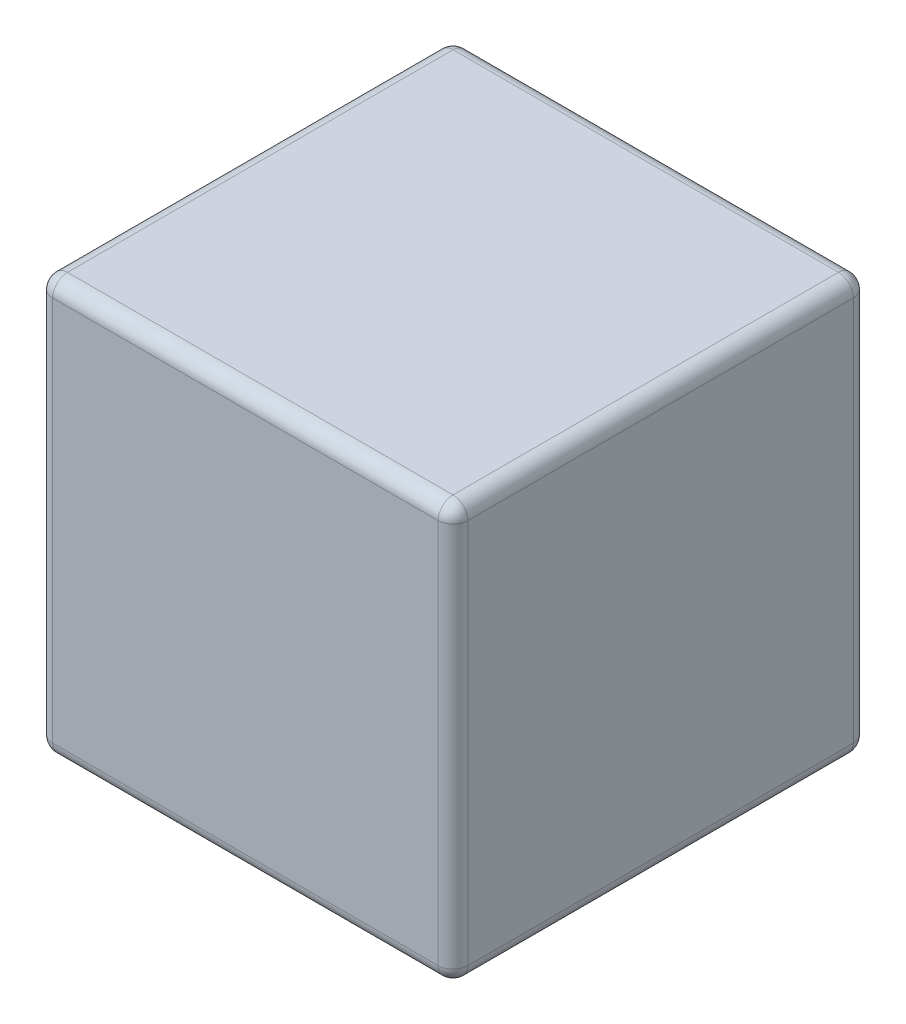
SolidWorks part; units mm, degrees
ref_plane "Front" through (0, 0, 0) normal (0, 0, 1) x (1, 0, 0)
ref_plane "Top" through (0, 0, 0) normal (0, 1, 0) x (1, 0, 0)
ref_plane "Right" through (0, 0, 0) normal (1, 0, 0) x (0, 0, -1)
sketch "Sketch1" plane through (0, 0, 0) normal (0, 1, 0) x (1, 0, 0)
  line L1 (-28, 28) -> (28, 28)
  line L2 (-28, 28) -> (-28, -28)
  line L3 (-28, -28) -> (28, -28)
  line L4 (28, 28) -> (28, -28)
  line L5 (-28, 28) -> (28, -28) construction
  line L6 (-28, -28) -> (28, 28) construction
  point P0 (0, 0)
  dimension "D1" = 56
  dimension "D2" = 56
extrude "Boss-Extrude1" add sketch "Sketch1" along normal mid plane 56
fillet "Fillet1" radius 2 12 edges at (-28, 0, -28) (28, 0, -28) (-28, 0, 28) (28, 0, 28) (0, -28, -28) (-28, -28, 0) (0, -28, 28) (28, -28, 0) (0, 28, 28) (-28, 28, 0) (0, 28, -28) (28, 28, 0)
